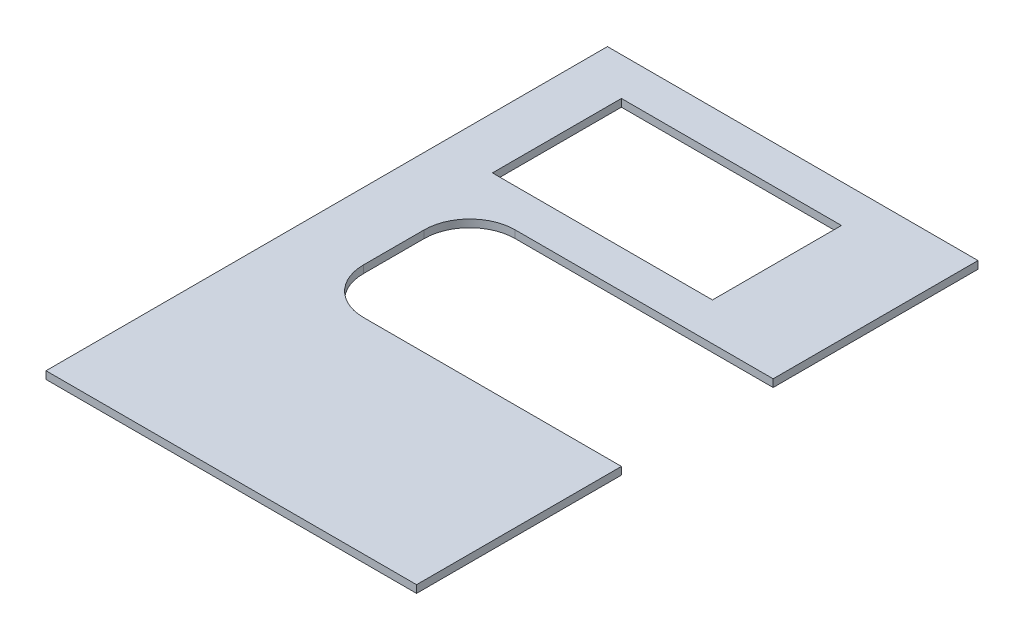
SolidWorks part; units mm, degrees
ref_plane "Front Plane" through (0, 0, 0) normal (0, 0, 1) x (1, 0, 0)
ref_plane "Top Plane" through (0, 0, 0) normal (0, 1, 0) x (1, 0, 0)
ref_plane "Right Plane" through (0, 0, 0) normal (1, 0, 0) x (0, 0, -1)
sketch "Sketch1" plane through (0, 0, 0) normal (0, 1, 0) x (1, 0, 0)
  line L1 (0, 0) -> (310.134, 0)
  line L2 (0, 0) -> (0, 469.9)
  line L3 (0, 469.9) -> (310.134, 469.9)
  line L4 (310.134, 0) -> (310.134, 469.9)
  dimension "D1" = 310.134
  dimension "D2" = 469.9
extrude "Boss-Extrude1" add sketch "Sketch1" along normal blind 6.35
ref_plane "Plane1" through (0, 0, -234.95) normal (0, 0, -1) x (-1, 0, 0)
ref_plane "Plane2" through (155.067, 0, 0) normal (1, 0, 0) x (0, 0, -1)
sketch "Sketch2" plane through (0, 6.35, 0) normal (0, 1, 0) x (1, 0, 0)
  line L0 (310.134, 0) -> (310.134, 469.9) construction
  line L1 (56.134, 171.45) -> (310.134, 171.45)
  line L2 (56.134, 171.45) -> (56.134, 298.45)
  line L3 (56.134, 298.45) -> (310.134, 298.45)
  line L4 (310.134, 171.45) -> (310.134, 298.45)
  line L5 (3.4925, 234.95) -> (-3.4925, 234.95) construction
  dimension "D1" = 63.5
  dimension "D2" = 63.5
  dimension "D3" = 254
extrude "Cut-Extrude1" cut sketch "Sketch2" against normal through all
fillet "Fillet1" radius 38.1 2 edges at (56.134, 3.175, -298.45) (56.134, 3.175, -171.45)
sketch "Sketch3" plane through (0, 6.35, 0) normal (0, 1, 0) x (1, 0, 0)
  line L0 (310.134, 384.175) -> (0, 384.175) construction
  line L1 (43.434, 330.2) -> (227.584, 330.2)
  line L2 (43.434, 330.2) -> (43.434, 438.15)
  line L3 (43.434, 438.15) -> (227.584, 438.15)
  line L4 (227.584, 330.2) -> (227.584, 438.15)
  line L5 (310.134, 298.45) -> (310.134, 469.9) construction
  line L6 (0, 469.9) -> (0, 0) construction
  line L7 (43.434, 384.175) -> (227.584, 384.175) construction
  dimension "D1" = 107.95
  dimension "D2" = 0
  dimension "D3" = 82.55
  dimension "D4" = 184.15
extrude "Cut-Extrude2" cut sketch "Sketch3" against normal through all
